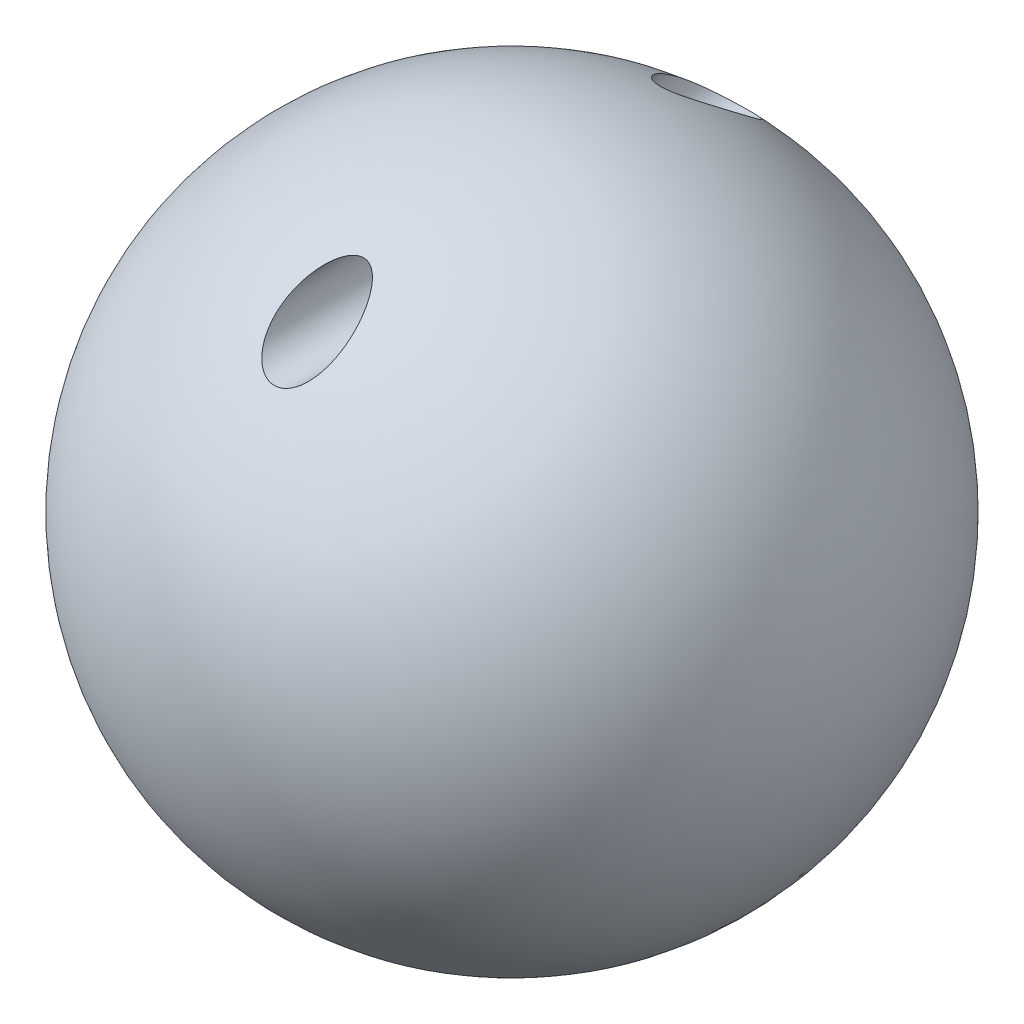
SolidWorks part; units mm, degrees
ref_plane "Front Plane" through (0, 0, 0) normal (0, 0, 1) x (1, 0, 0)
ref_plane "Top Plane" through (0, 0, 0) normal (0, 1, 0) x (1, 0, 0)
ref_plane "Right Plane" through (0, 0, 0) normal (1, 0, 0) x (0, 0, -1)
sketch "Sketch1" plane through (0, 0, 0) normal (0, 0, 1) x (1, 0, 0)
  line L0 (0, 0) -> (0, 25.4)
  arc A0 (0, 25.4) -> (0, 0) centre (0, 12.7) cw
  point P4 (0, 0)
  point P5 (0, 12.7)
  dimension "D1" = 25.4
revolve "Revolve1" add sketch "Sketch1" angle 360 about L0
sketch "Sketch2" plane through (0, 0, 0) normal (0, 0, 1) x (1, 0, 0)
  line L0 (0, 0) -> (0, 25.4) construction
  circle A0 centre (0, 22.7704) radius 1.27
  dimension "D1" = 2.54
extrude "Cut-Extrude3" cut sketch "Sketch2" against normal through all both and the other way through all
